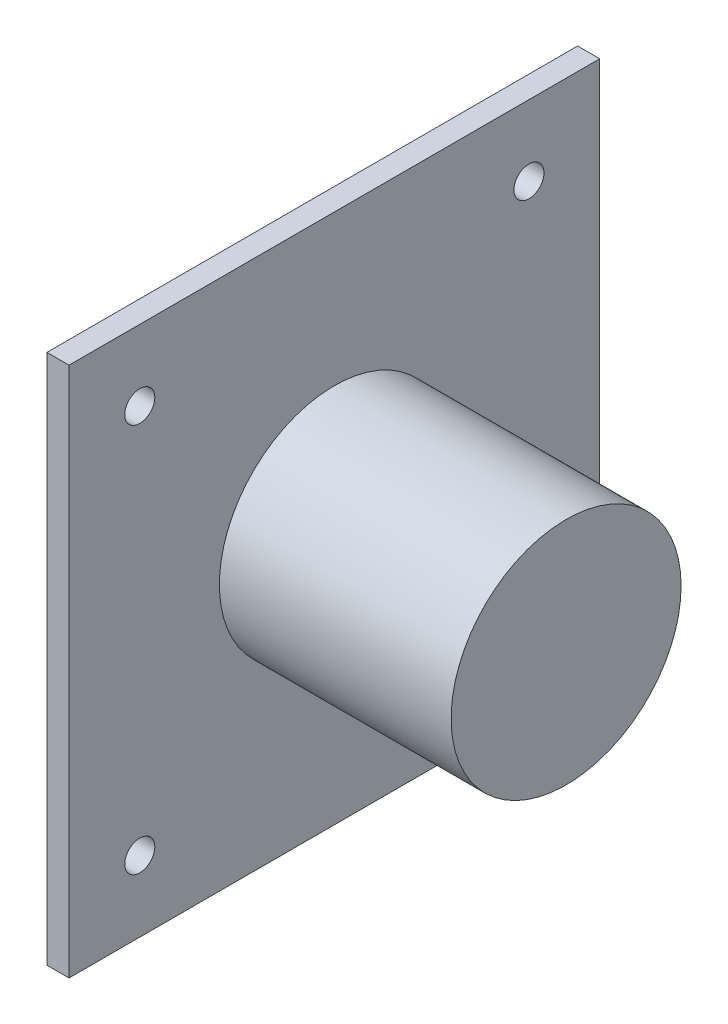
SolidWorks part; units mm, degrees
material "6061-T6 (SS)"
ref_plane "Front Plane" through (0, 0, 0) normal (0, 0, 1) x (1, 0, 0)
ref_plane "Top Plane" through (0, 0, 0) normal (0, 1, 0) x (1, 0, 0)
ref_plane "Right Plane" through (0, 0, 0) normal (1, 0, 0) x (0, 0, -1)
sketch "Sketch1" plane through (0, 0, 0) normal (1, 0, 0) x (0, 0, -1)
  line L0 (13.97, -13.97) -> (13.97, 13.97) construction
  line L1 (-19.05, -19.05) -> (19.05, -19.05)
  line L2 (-19.05, -19.05) -> (-19.05, 19.05)
  line L3 (-19.05, 19.05) -> (19.05, 19.05)
  line L4 (19.05, -19.05) -> (19.05, 19.05)
  line L5 (-19.05, -19.05) -> (19.05, 19.05) construction
  line L6 (-19.05, 19.05) -> (19.05, -19.05) construction
  line L11 (-12.7, -12.7) -> (12.7, 12.7) construction
  line L12 (-12.7, 12.7) -> (12.7, -12.7) construction
  line L13 (13.97, 13.97) -> (-13.97, 13.97) construction
  circle A0 centre (13.97, -13.97) radius 1.0795
  circle A1 centre (-13.97, -13.97) radius 1.0795
  circle A2 centre (-13.97, 13.97) radius 1.0795
  circle A3 centre (13.97, 13.97) radius 1.0795
  point P0 (0, 0)
  point P10 (0, 0)
  dimension "D3" = 2.159
  dimension "D1" = 38.1
  dimension "D2" = 27.94
extrude "Boss-Extrude1" add sketch "Sketch1" along normal blind 1.5875
sketch "Sketch2" plane through (1.5875, 0, 0) normal (1, 0, 0) x (0, 0, -1)
  line L5 (-12.7, -12.7) -> (12.7, -12.7)
  line L6 (-12.7, -12.7) -> (-12.7, 12.7)
  line L7 (-12.7, 12.7) -> (12.7, 12.7)
  line L8 (12.7, -12.7) -> (12.7, 12.7)
  line L9 (-12.7, -12.7) -> (12.7, 12.7) construction
  line L10 (-12.7, 12.7) -> (12.7, -12.7) construction
  point P4 (0, 0)
  dimension "D1" = 25.4
sketch "Sketch3" plane through (0, 0, 0) normal (-1, 0, 0) x (0, 0, 1)
  line L1 (-11.43, -15.24) -> (-1.27, -15.24)
  line L2 (-11.43, -15.24) -> (-11.43, -10.16)
  line L3 (-11.43, -10.16) -> (-1.27, -10.16)
  line L4 (-1.27, -15.24) -> (-1.27, -10.16)
  line L5 (-11.43, -15.24) -> (-1.27, -10.16) construction
  line L6 (-11.43, -10.16) -> (-1.27, -15.24) construction
  line L8 (19.05, -19.05) -> (-19.05, -19.05) construction
  line L9 (-19.05, -19.05) -> (-19.05, 19.05) construction
  point P4 (-6.35, -12.7)
  dimension "D1" = 5.08
  dimension "D2" = 10.16
  dimension "D3" = 3.81
  dimension "D4" = 7.62
extrude "Boss-Extrude2" add sketch "Sketch3" along normal blind 8.89
sketch "Sketch4" plane through (1.5875, 0, 0) normal (1, 0, 0) x (0, 0, -1)
  circle A0 centre (0, 0) radius 8.255
  dimension "D1" = 16.51
extrude "Boss-Extrude3" add sketch "Sketch4" along normal blind 16.637
